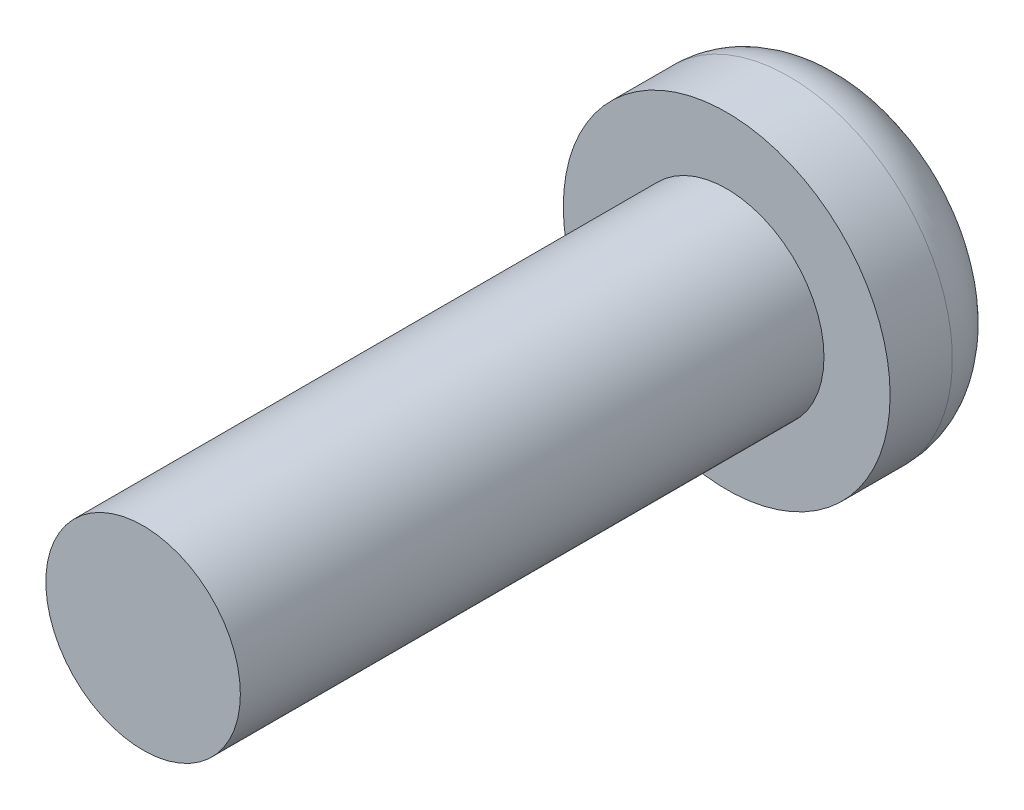
SolidWorks part; units mm, degrees
ref_plane "Front Plane" through (0, 0, 0) normal (0, 0, 1) x (1, 0, 0)
ref_plane "Top Plane" through (0, 0, 0) normal (0, 1, 0) x (1, 0, 0)
ref_plane "Right Plane" through (0, 0, 0) normal (1, 0, 0) x (0, 0, -1)
sketch "Sketch1" plane through (0, 0, 0) normal (0, 0, 1) x (1, 0, 0)
  circle A0 centre (0, 0) radius 2.1
  dimension "D1" = 4.2
extrude "Boss-Extrude1" add sketch "Sketch1" along normal blind 1.6
sketch "Sketch2" plane through (0, 0, 0) normal (0, 1, 0) x (1, 0, 0)
  line L0 (-2.1, 0) -> (-2.1, -1.6) construction
  line L1 (2.1, 0) -> (-2.1, 0) construction
  line L2 (-2.1, -0.8) -> (-2.1, 0)
  line L3 (-2.1, 0) -> (-1.3, 0)
  line L4 (0, 0) -> (0, -1.6) construction
  line L5 (-2.1, -1.6) -> (2.1, -1.6) construction
  arc A0 (-1.3, 0) -> (-2.1, -0.8) centre (-1.3, -0.8) ccw
  dimension "D1" = 0.8
revolve "Cut-Revolve1" cut sketch "Sketch2" angle 360 about L4
sketch "Sketch3" plane through (0, 0, 0) normal (0, 0, -1) x (-1, 0, 0)
  line L0 (0.88, 0) -> (-0.88, 0) construction
  line L1 (-0.25, 1) -> (0.25, 1)
  line L2 (-0.25, 1) -> (-0.25, -1)
  line L3 (-0.25, -1) -> (0.25, -1)
  line L4 (0.25, 1) -> (0.25, -1)
  line L5 (-1, 0.25) -> (1, 0.25)
  line L6 (-1, 0.25) -> (-1, -0.25)
  line L7 (-1, -0.25) -> (1, -0.25)
  line L8 (1, 0.25) -> (1, -0.25)
  dimension "D1" = 1
  dimension "D2" = 2
  dimension "D3" = 2
  dimension "D4" = 1
  dimension "D5" = 0.5
  dimension "D6" = 0.5
  dimension "D7" = 0.25
  dimension "D8" = 0.25
extrude "Cut-Extrude1" cut sketch "Sketch3" against normal blind 0.5 contours L7 L2 L3 L4 | L8 L5 L4 L7 | L6 L7 L2 L5 | L2 L5 L4 L1 | L2 L7 L4 L5
sketch "Sketch4" plane through (0, 0, 1.6) normal (0, 0, 1) x (1, 0, 0)
  circle A0 centre (0, 0) radius 1.25
  dimension "D1" = 2.5
extrude "Boss-Extrude2" add sketch "Sketch4" along normal blind 7.5
